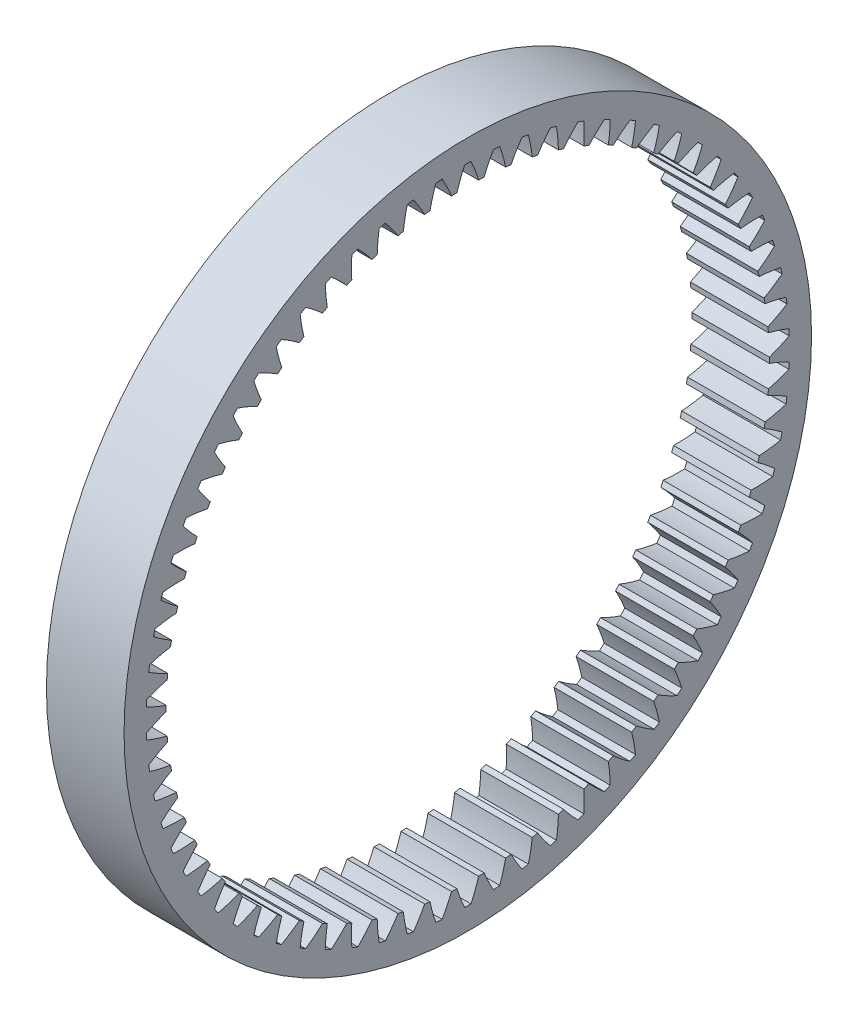
SolidWorks part; units mm, degrees
ref_plane "Plane1" through (0, 0, 0) normal (0, 0, 1) x (1, 0, 0)
ref_plane "Plane2" through (0, 0, 0) normal (0, 1, 0) x (1, 0, 0)
ref_plane "Plane3" through (0, 0, 0) normal (1, 0, 0) x (0, 0, -1)
other "Configuration Table"
sketch "HoldingSke" plane through (0, 0, 0) normal (0, 1, 0) x (1, 0, 0)
  line L0 (0, 0) -> (0.4275, -1.1746)
  line L1 (-15, 0) -> (100, 0) construction
  line L2 (0, 0) -> (-2.1039, 2.3779)
  line L3 (0, 0) -> (-11.863, 4.5341)
  line L4 (0, 0) -> (2.9537, 8.1152)
  line L5 (0, 0) -> (-23.7986, -8.8762)
  line L6 (0, 0) -> (-10.5278, -7.1032)
  line L7 (-2.1039, 2.3779) -> (3.3635, 27.1825)
  line L8 (-76.2, 3.1779) -> (-54.61, 3.1779)
  line L9 (-71.009, 38.7566) -> (-53.1078, 45.2721)
  line L10 (-76.2, 71.12) -> (104.1128, 71.12)
  line L11 (0, 0) -> (-7, 0)
  line L12 (-76.2, 101.6) -> (-76.17, 101.6)
  line L13 (24.9733, 27.94) -> (52.9518, 28.4284)
  line L14 (24.9733, 27.94) -> (24.9743, 27.94)
  line L15 (24.9733, 27.94) -> (100.4006, 29.5858)
  circle A0 centre (0, 0) radius 31
  circle A1 centre (0, 0) radius 12.7
  circle A2 centre (0, 0) radius 12.7
  dimension "MHD" = 25.4
  dimension "Hub_dia" = 25.4
  dimension "Diameter" = 62
  dimension "Num_teeth" = 70
  dimension "Pitch" = 1.25
  dimension "Overall_len" = 25.4
  dimension "Show_teeth" = 70
  dimension "Thickness" = 12.7
  dimension "OAL" = 25.4001
  dimension "T_dim" = 21.59
  dimension "Ap" = 20
  dimension "H" = 19.05
  dimension "Pitch_radius" = 180.3128
  dimension "Width" = 7
  dimension "Backlash" = 0.03
  dimension "Addendum_fac" = 1
  dimension "Dedendum_fac" = 1.25
  dimension "Clearance_fac" = 0.25
  dimension "Dedendum_add" = 0.001
  dimension "Module" = 0.8
sketch "BasProSke" plane through (0, 0, 0) normal (0, 1, 0) x (1, 0, 0)
  line L0 (-10, 0) -> (60, 0) construction
  line L1 (0, 27.2) -> (0, 31)
  line L2 (0, 27.2) -> (7, 27.2)
  line L3 (7, 27.2) -> (7, 31)
  line L4 (7, 31) -> (0, 31)
  dimension "Diameter" = 62
  dimension "Thickness" = 7
  dimension "Inside_diameter" = 54.4
revolve "Base-Revolve" add sketch "BasProSke" angle 360 about L0
sketch "TooCutSke" plane through (0, 0, 0) normal (1, 0, 0) x (0, 0, -1)
  line L3 (0.7033, 27.9912) -> (0.7033, 53.6633) construction
  line L4 (0, 0) -> (0, 59.563) construction
  line L5 (0, 0) -> (-3.0655, 68.2587) construction
  line L6 (-12.4315, 23.1458) -> (36.7423, 25.3542) construction
  circle A0 centre (0, 0) radius 28 construction
  circle A1 centre (0, 0) radius 29.001 construction
  circle A2 centre (0, 0) radius 23.6803 construction
  circle A3 centre (0, 0) radius 27.1746 construction
  arc A4 (0.9816, 27.1569) -> (0.2859, 28.9996) centre (-12.4315, 23.1458) ccw
  arc A5 (0.9816, 27.1569) -> (-0.9816, 27.1569) centre (0, 0) ccw
  arc A6 (0.2859, 28.9996) -> (-0.2859, 28.9996) centre (0, 0) ccw
  arc A7 (-0.2859, 28.9996) -> (-0.9816, 27.1569) centre (12.4315, 23.1458) ccw
  dimension "Pitch_dia" = 56
  dimension "Base_dia" = 47.3605
  dimension "Root_dia" = 58.002
  dimension "Overcut_dia" = 54.3492
  dimension "Flank_rad" = 14
  dimension "Half_ang" = 2.571
  dimension "Half_CT" = 0.7033
extrude "ToothCut" cut sketch "TooCutSke" along normal through all
fillet "Breaks" [suppressed] radius 0.08
fillet "RootFillets" [suppressed] radius 0.201
pattern_circular "TeethCuts" count 70 every 5.143 about axis through (-10, 0, 0) along (1, 0, 0) of "RootFillets", "Breaks", "ToothCut"
equation "' \"Module@HoldingSke\" = 6.35"
equation "' \"Num_teeth@HoldingSke\" = 24"
equation "' \"Ap@HoldingSke\" =  14.5"
equation "' \"Ap@HoldingSke\" = 14.5"
equation "' \"Width@HoldingSke\" = 12"
equation "' \"Diameter@HoldingSke\" = 8 * 25.4"
equation "' \"Show_teeth@HoldingSke\" = 100"
equation "' \"Backlash@HoldingSke\" = 0.009 * 25.4"
equation "' \"Addendum_fac@HoldingSke\" = 1.0"
equation "' \"Dedendum_fac@HoldingSke\" = 1.25"
equation "' \"Dedendum_add@HoldingSke\" = 0.00005 * 25.4"
equation "' \"Clearance_fac@HoldingSke\" = 0.25"
equation "\"Pitch@HoldingSke\" = 1 / \"Module@HoldingSke\" "
equation "\"Overcut_dia@TooCutSke\" = (\"Num_teeth@HoldingSke\" - 2 * \"Addendum_fac@HoldingSke\") / \"Pitch@HoldingSke\" - 0.002 * 25.4"
equation "\"Pitch_dia@TooCutSke\" = \"Num_teeth@HoldingSke\" / \"Pitch@HoldingSke\""
equation "\"Base_dia@TooCutSke\" = \"Num_teeth@HoldingSke\" / \"Pitch@HoldingSke\" * cos((\"Ap@HoldingSke\"  * 3.14159265 / 180)) * 0.90"
equation "\"Root_dia@TooCutSke\" = \"Num_teeth@HoldingSke\"  / \"Pitch@HoldingSke\" + 2 *  \"Dedendum_fac@HoldingSke\"/ \"Pitch@HoldingSke\" + \"Dedendum_add@HoldingSke\" * 2"
equation "\"Half_ang@TooCutSke\" = 180 / \"Num_teeth@HoldingSke\""
equation "\"Half_CT@TooCutSke\" = \"Num_teeth@HoldingSke\" / \"Pitch@HoldingSke\" * sin((3.14159265 / 2 / \"Num_teeth@HoldingSke\")) / 2 + 10 * \"Backlash@HoldingSke\" / 4"
equation "\"Flank_rad@TooCutSke\" = \"Num_teeth@HoldingSke\" / \"Pitch@HoldingSke\" / 4"
equation "\"Radius@RootFillets\"= \"Clearance_fac@HoldingSke\" / \"Pitch@HoldingSke\" + \"Dedendum_add@HoldingSke\""
equation "\"Break_rad@Breaks\" = 0.02 / \"Pitch@HoldingSke\" * 5"
equation "\"Num_teeth@TeethCuts\" = int( \"Show_teeth@HoldingSke\" ) + 1"
equation "\"Num_teeth@TeethCuts\" = ((sgn( \"Num_teeth@TeethCuts\" - \"Num_teeth@HoldingSke\" )-1)*( \"Num_teeth@TeethCuts\" - \"Num_teeth@HoldingSke\" ))/-2+ \"Num_teeth@HoldingSke\""
equation "\"Num_teeth@TeethCuts\" = ((sgn( \"Num_teeth@TeethCuts\" - 2.0)+1)*( \"Num_teeth@TeethCuts\" - 2.0))/2 +2.0"
equation "\"Angle@TeethCuts\" = 360.0 / \"Num_teeth@HoldingSke\""
equation "\"Diameter@BasProSke\" = \"Num_teeth@HoldingSke\"  / \"Pitch@HoldingSke\" + 2 *  \"Dedendum_fac@HoldingSke\"/ \"Pitch@HoldingSke\" + \"Dedendum_add@HoldingSke\" * 2 + 0.002 * 25.4"
equation "\"Diameter@BasProSke\" = ((sgn( \"Diameter@BasProSke\"  - \"Diameter@HoldingSke\" )+1)*( \"Diameter@BasProSke\"  - \"Diameter@HoldingSke\" ))/2 + \"Diameter@HoldingSke\""
equation "\"Inside_diameter@BasProSke\" =  (\"Num_teeth@HoldingSke\" - 2 * \"Addendum_fac@HoldingSke\") / \"Pitch@HoldingSke\" "
equation "\"Thickness@BasProSke\"  = \"Width@HoldingSke\""
